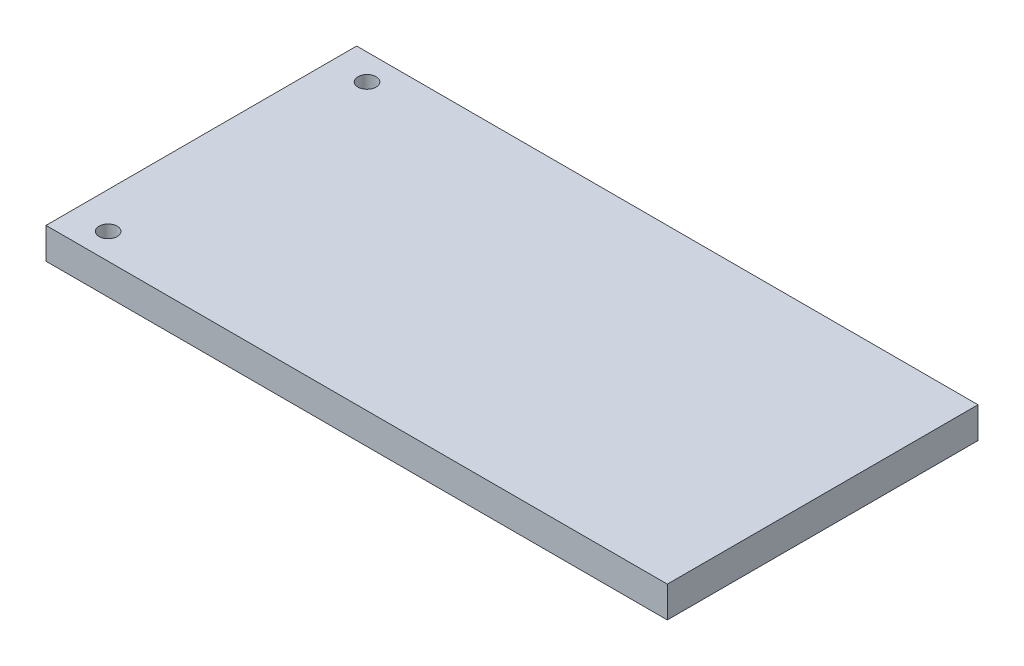
SolidWorks part; units mm, degrees
material "天然橡胶"
ref_plane "前视基准面" through (0, 0, 0) normal (0, 0, 1) x (1, 0, 0)
ref_plane "上视基准面" through (0, 0, 0) normal (0, 1, 0) x (1, 0, 0)
ref_plane "右视基准面" through (0, 0, 0) normal (1, 0, 0) x (0, 0, -1)
other "Configuration Table"
sketch "草图1" plane through (0, 0, 0) normal (0, 1, 0) x (1, 0, 0)
  line L0 (0, 0) -> (-60, 0)
  line L1 (0, 0) -> (60, 0)
  line L2 (60, 0) -> (60, -60)
  line L3 (60, -60) -> (-60, -60)
  line L4 (-60, -60) -> (-60, 0)
extrude "凸台-拉伸1" add sketch "草图1" along normal blind 6
sketch "草图2" plane through (0, 6, 0) normal (0, 1, 0) x (1, 0, 0)
  line L0 (-60, 0) -> (-53, 0)
  line L1 (60, 0) -> (-60, 0) construction
  line L2 (-53, 0) -> (-53, -60)
  line L3 (-60, -60) -> (60, -60) construction
  line L4 (-53, 0) -> (-53, -5)
  line L5 (-53, -60) -> (-53, -55)
  circle A0 centre (-53, -5) radius 1.75
  circle A1 centre (-53, -55) radius 1.75
extrude "切除-拉伸1" cut sketch "草图2" against normal blind 6 contours L4 A0 L2 | L2 A0 L4 | L2 A1 | L2 A1
